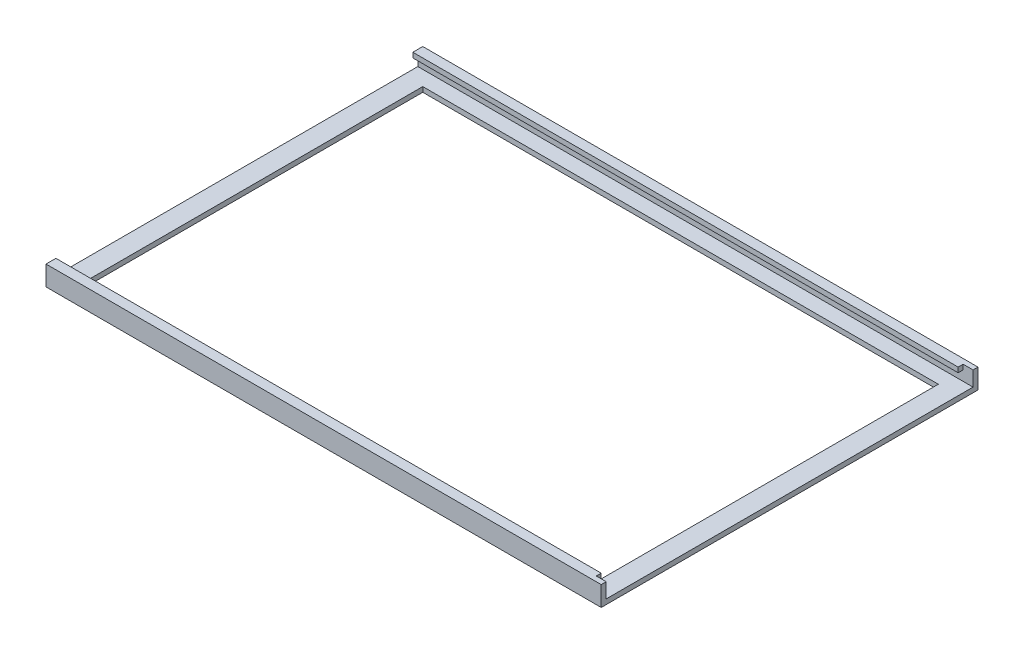
SolidWorks part; units mm, degrees
ref_plane "Alzado" through (0, 0, 0) normal (0, 0, 1) x (1, 0, 0)
ref_plane "Planta" through (0, 0, 0) normal (0, 1, 0) x (1, 0, 0)
ref_plane "Vista lateral" through (0, 0, 0) normal (1, 0, 0) x (0, 0, -1)
sketch "Croquis1" plane through (0, 0, 0) normal (0, 1, 0) x (1, 0, 0)
  line L0 (0, 0) -> (112, 0)
  line L1 (112, 0) -> (112, 76)
  line L2 (112, 76) -> (0, 76)
  line L3 (0, 76) -> (0, 0)
  line L4 (4, 72) -> (108, 72)
  line L5 (108, 72) -> (108, 4)
  line L6 (108, 4) -> (4, 4)
  line L7 (4, 4) -> (4, 72)
  point P7 (0, 0)
  point P10 (0, 0)
  point P11 (0, 0)
  point P12 (0, 0)
  dimension "D1" = 76
  dimension "D2" = 112
  dimension "D3" = 4
  dimension "D4" = 4
  dimension "D5" = 4
  dimension "D6" = 4
extrude "Saliente-Extruir3" add sketch "Croquis1" along normal blind 1 contours L3 L0 L1 L2 | L7 L4 L5 L6
sketch "Croquis2" plane through (0, 1, 0) normal (0, 1, 0) x (1, 0, 0)
  line L0 (112, 76) -> (112, 75)
  line L1 (112, 0) -> (112, 76) construction
  line L2 (112, 75) -> (0, 75)
  line L3 (0, 76) -> (0, 0) construction
  line L4 (0, 75) -> (0, 76)
  line L5 (0, 76) -> (112, 76)
  line L6 (112, 75) -> (112, 1) construction
  line L7 (112, 1) -> (112, 0)
  line L8 (112, 0) -> (0, 0)
  line L9 (0, 0) -> (0, 1)
  line L10 (0, 1) -> (112, 1)
  point P5 (0, 0)
  point P15 (0, 0)
  point P19 (0, 0)
  point P20 (0, 0)
  point P21 (0, 0)
  point P22 (0, 0)
  dimension "D1" = 1
  dimension "D2" = 1
extrude "Saliente-Extruir4" add sketch "Croquis2" along normal blind 3 contours L10 L7 L8 L9 | L2 L4 L5 L0
sketch "Croquis3" plane through (0, 0, -1) normal (0, 0, -1) x (-1, 0, 0)
  line L0 (0, 4) -> (0, 1) construction
  line L1 (0, 4) -> (0, 3)
  line L2 (0, 4) -> (-112, 4) construction
  line L3 (0, 3) -> (-110, 3)
  line L4 (-110, 3) -> (-110, 4)
  line L5 (-110, 4) -> (0, 4)
  dimension "D1" = 2
  dimension "D2" = 1
extrude "Saliente-Extruir7" add sketch "Croquis3" along normal blind 1 contours L3 L4 L5 L1
sketch "Croquis5" plane through (0, 0, -75) normal (0, 0, 1) x (1, 0, 0)
  line L0 (0, 4) -> (0, 3)
  line L1 (0, 4) -> (0, 1) construction
  line L2 (0, 3) -> (110, 3)
  line L3 (110, 3) -> (110, 4)
  line L4 (112, 4) -> (0, 4) construction
  line L5 (110, 4) -> (0, 4)
  dimension "D1" = 1
  dimension "D2" = 2
extrude "Saliente-Extruir8" add sketch "Croquis5" along normal blind 1
